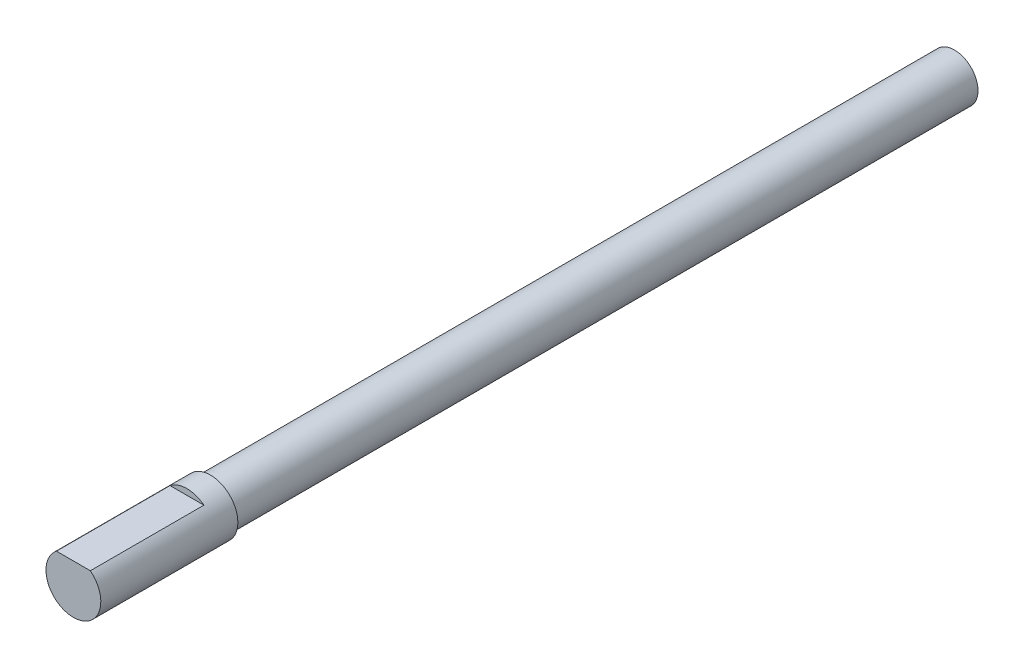
SolidWorks part; units mm, degrees
ref_plane "Plan de face" through (0, 0, 0) normal (0, 0, 1) x (1, 0, 0)
ref_plane "Plan de dessus" through (0, 0, 0) normal (0, 1, 0) x (1, 0, 0)
ref_plane "Plan de droite" through (0, 0, 0) normal (1, 0, 0) x (0, 0, -1)
sketch "Esquisse1" plane through (0, 0, 0) normal (0, 0, 1) x (1, 0, 0)
  circle A0 centre (0, 0) radius 6
  dimension "D1" = 12
extrude "Boss.-Extru.1" add sketch "Esquisse1" along normal blind 190
sketch "Esquisse2" plane through (0, 0, 190) normal (0, 0, 1) x (1, 0, 0)
  circle A0 centre (0, 0) radius 7
  dimension "D1" = 14
extrude "Boss.-Extru.2" add sketch "Esquisse2" along normal blind 35
sketch "Esquisse3" plane through (0, 0, 0) normal (0, 0, -1) x (-1, 0, 0)
  circle A0 centre (0, 0) radius 3
extrude "Enlèv. mat.-Extru.1" cut sketch "Esquisse3" against normal blind 20
sketch "Esquisse4" plane through (0, 0, 225) normal (0, 0, 1) x (1, 0, 0)
  line L5 (-4.6425, 5.5) -> (5.4059, 5.5)
  line L6 (-4.6425, 5.5) -> (-4.6425, 10.5)
  line L7 (-4.6425, 10.5) -> (5.4059, 10.5)
  line L8 (5.4059, 5.5) -> (5.4059, 10.5)
  dimension "D3" = 5
  dimension "D4" = 5.5
extrude "Enlèv. mat.-Extru.2" cut sketch "Esquisse4" against normal blind 29
